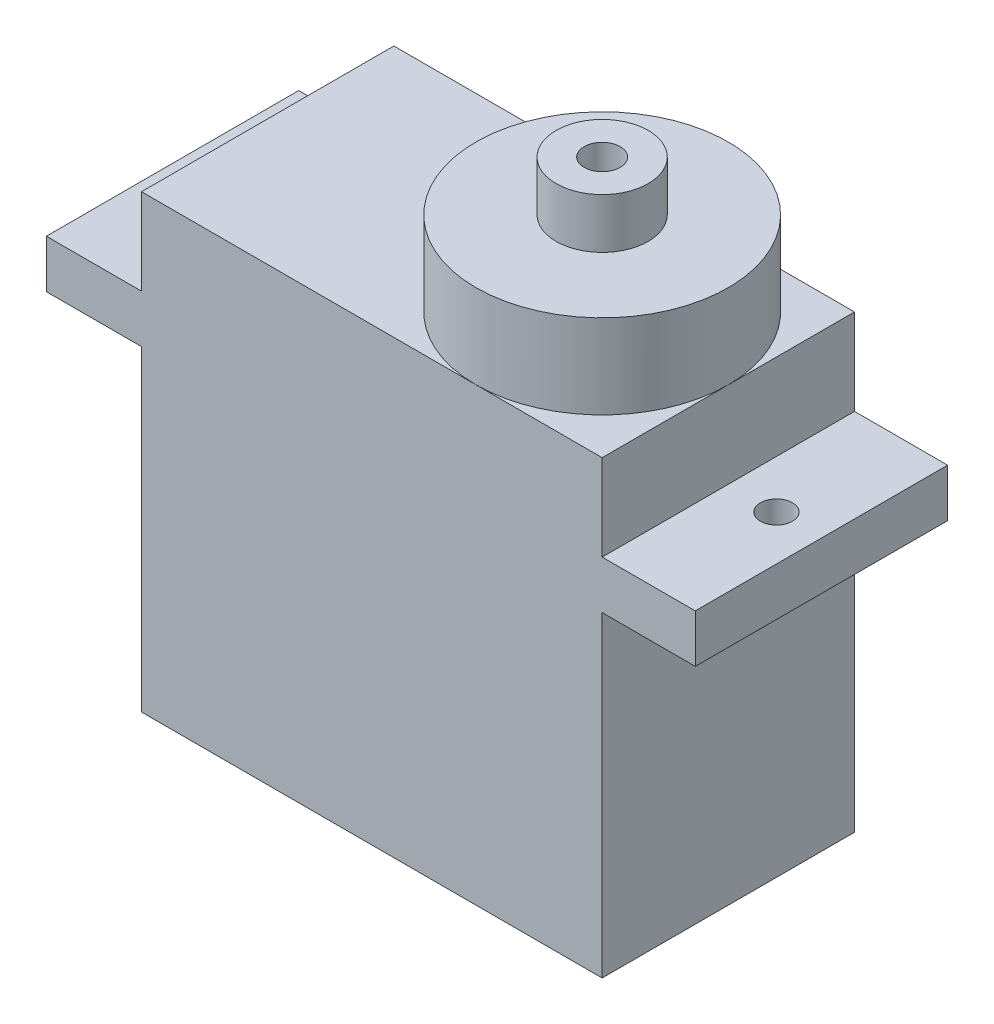
SolidWorks part; units mm, degrees
ref_plane "正面" through (0, 0, 0) normal (0, 0, 1) x (1, 0, 0)
ref_plane "平面" through (0, 0, 0) normal (0, 1, 0) x (1, 0, 0)
ref_plane "右側面" through (0, 0, 0) normal (1, 0, 0) x (0, 0, -1)
sketch "ｽｹｯﾁ5" plane through (0, 0, 0) normal (0, 0, 1) x (1, 0, 0)
  line L1 (-11.5, 11.25) -> (11.5, 11.25)
  line L2 (-11.5, 11.25) -> (-11.5, -11.25)
  line L3 (-11.5, -11.25) -> (11.5, -11.25)
  line L4 (11.5, 11.25) -> (11.5, -11.25)
  line L5 (-11.5, 11.25) -> (11.5, -11.25) construction
  line L6 (-11.5, -11.25) -> (11.5, 11.25) construction
  point P0 (0, 0)
  dimension "D1" = 22.5
  dimension "D2" = 23
extrude "ﾎﾞｽ - 押し出し4" add sketch "ｽｹｯﾁ5" along normal blind 12.6
sketch "ｽｹｯﾁ6" plane through (0, 0, 0) normal (0, 0, 1) x (1, 0, 0)
  line L0 (-11.5, -11.25) -> (11.5, -11.25) construction
  line L1 (-16.25, 6.95) -> (16.15, 6.95)
  line L2 (-16.25, 6.95) -> (-16.25, 4.55)
  line L3 (-16.25, 4.55) -> (16.15, 4.55)
  line L4 (16.15, 6.95) -> (16.15, 4.55)
  line L5 (-16.25, 6.95) -> (16.15, 4.55) construction
  line L6 (-16.25, 4.55) -> (16.15, 6.95) construction
  point P0 (-0.05, 5.75)
  dimension "D1" = 15.8
  dimension "D2" = 2.4
  dimension "D3" = 32.4
  dimension "D4" = 16.15
extrude "ﾎﾞｽ - 押し出し5" add sketch "ｽｹｯﾁ6" along normal blind 12.6 contours L2 L1 L4 L3
ref_plane "平面1" through (0, 11.25, 0) normal (0, 1, 0) x (1, 0, 0)
sketch "ｽｹｯﾁ7" plane through (0, 11.25, 0) normal (0, 1, 0) x (1, 0, 0)
  line L0 (11.5, -12.6) -> (-11.5, -12.6) construction
  line L1 (11.5, -12.6) -> (11.5, 0) construction
  circle A0 centre (5.2, -6.3) radius 6.3
  dimension "D1" = 12.6
  dimension "D2" = 6.3
  dimension "D3" = 6.3
extrude "ﾎﾞｽ - 押し出し6" add sketch "ｽｹｯﾁ7" along normal blind 4.2
ref_plane "平面2" through (0, 15.45, 0) normal (0, 1, 0) x (1, 0, 0)
sketch "ｽｹｯﾁ9" plane through (0, 15.45, 0) normal (0, 1, 0) x (1, 0, 0)
  circle A0 centre (5.2, -6.3) radius 2.3
extrude "ﾎﾞｽ - 押し出し8" add sketch "ｽｹｯﾁ9" along normal blind 2.5
sketch "ｽｹｯﾁ10" plane through (0, 15.45, 0) normal (0, 1, 0) x (1, 0, 0)
  circle A0 centre (5.2, -6.3) radius 0.9
extrude "ｶｯﾄ - 押し出し1" cut sketch "ｽｹｯﾁ10" along normal blind 2.5
hole_wizard "M2x0.4 ねじ穴1" positions "ｽｹｯﾁ11" profile "ｽｹｯﾁ12" tap size "M2x0.4" standard "JIS" end condition through all
sketch "ｽｹｯﾁ11" plane through (0, 6.95, 0) normal (0, 1, 0) x (1, 0, 0)
  line L0 (11.5, 0) -> (16.15, 0) construction
  line L1 (-16.25, 0) -> (-11.5, 0) construction
  point P0 (-13.9, -6.3)
  point P2 (13.9, -6.3)
  dimension "D1" = 13.9
  dimension "D2" = 13.9
  dimension "D3" = 6.3
  dimension "D4" = 6.3
sketch "ｽｹｯﾁ12" plane through (-13.9, 6.95, 6.3) normal (1, 0, 0) x (0, 0, 1)
  line L0 (0, 0) -> (0, 18.2)
  line L1 (0, 18.2) -> (0.8, 18.2)
  line L2 (0.8, 18.2) -> (0.8, 0)
  line L5 (0.8, 0) -> (0, 0)
  line L11 (0, -6.35) -> (0, 107.95) construction
  dimension "次ｻｰﾌｪｽまでのねじ下穴ﾄﾞﾘﾙ直径" = 1.6
  dimension "次ｻｰﾌｪｽまでのねじ下穴ﾄﾞﾘﾙの深さ" = 18.2
cosmetic thread "穴のねじ山1" parameters "D2"=2
cosmetic thread "穴のねじ山2" parameters "D2"=2
sketch "ｽｹｯﾁ8" plane through (0, 15.45, 0) normal (0, 1, 0) x (1, 0, 0)
  line L1 (3.2, -46.3) -> (7.2, -46.3)
  line L2 (3.2, -46.3) -> (3.2, 33.7)
  line L3 (3.2, 33.7) -> (7.2, 33.7)
  line L4 (7.2, -46.3) -> (7.2, 33.7)
  line L5 (3.2, -46.3) -> (7.2, 33.7) construction
  line L6 (3.2, 33.7) -> (7.2, -46.3) construction
  line L7 (-34.8, -4.3) -> (45.2, -4.3)
  line L8 (-34.8, -4.3) -> (-34.8, -8.3)
  line L9 (-34.8, -8.3) -> (45.2, -8.3)
  line L10 (45.2, -4.3) -> (45.2, -8.3)
  line L11 (-34.8, -4.3) -> (45.2, -8.3) construction
  line L12 (-34.8, -8.3) -> (45.2, -4.3) construction
  point P0 (5.2, -6.3)
  point P6 (5.2, -6.3)
  dimension "D1" = 4
  dimension "D2" = 80
  dimension "D3" = 4
  dimension "D4" = 80
